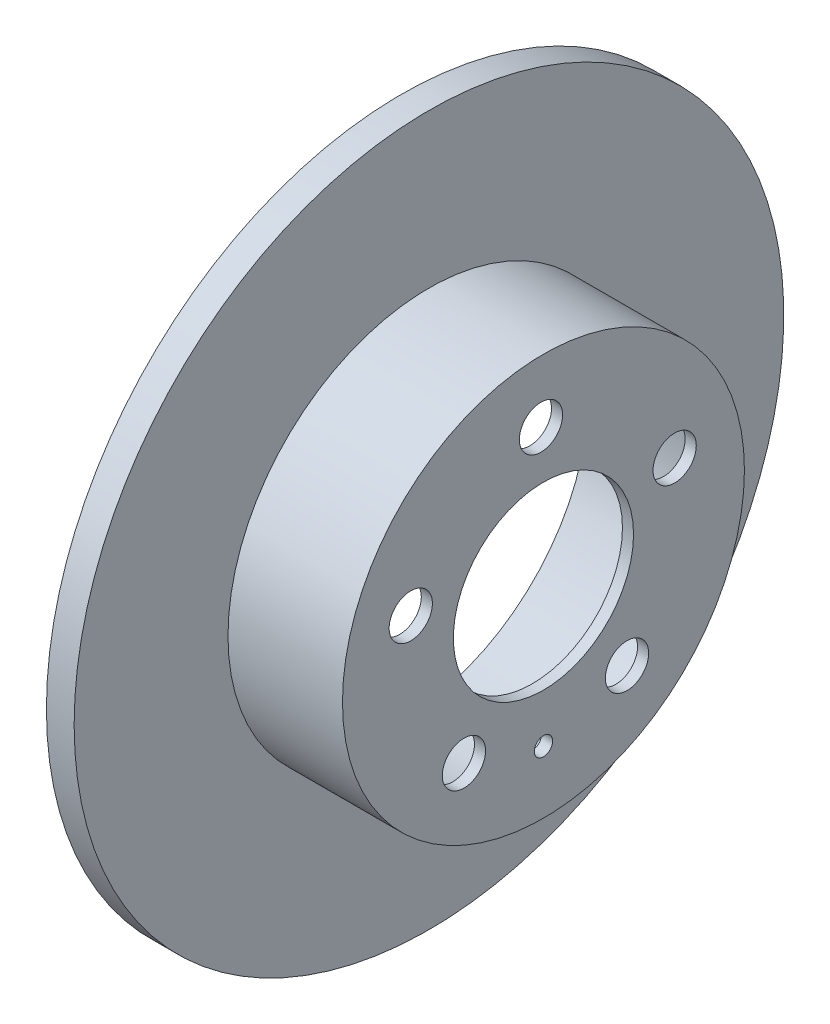
SolidWorks part; units mm, degrees
ref_plane "Płaszczyzna przednia" through (0, 0, 0) normal (0, 0, 1) x (1, 0, 0)
ref_plane "Płaszczyzna górna" through (0, 0, 0) normal (0, 1, 0) x (1, 0, 0)
ref_plane "Płaszczyzna prawa" through (0, 0, 0) normal (1, 0, 0) x (0, 0, -1)
sketch "Szkic1" plane through (0, 0, 0) normal (0, 1, 0) x (1, 0, 0)
  line L1 (0, 0) -> (10, 0)
  line L2 (0, 0) -> (0, 128)
  line L3 (0, 128) -> (10, 128)
  line L4 (10, 0) -> (10, 128)
  dimension "D1" = 10
  dimension "D2" = 128
revolve "Obrót1" add sketch "Szkic1" angle 360 about L1
sketch "Szkic7" plane through (10, 0, 0) normal (1, 0, 0) x (0, 0, -1)
  circle A0 centre (0, 0) radius 72.5
  dimension "D1" = 145
extrude "Dodanie-wyciągnięcie1" add sketch "Szkic7" along normal blind 41.3
sketch "Szkic8" plane through (0, 0, 0) normal (-1, 0, 0) x (0, 0, 1)
  circle A0 centre (0, 0) radius 67.5
  dimension "D1" = 135
sketch "Szkic9" plane through (51.3, 0, 0) normal (1, 0, 0) x (0, 0, -1)
  circle A0 centre (0, 0) radius 32.5
  dimension "D1" = 65
sketch "Szkic10" plane through (51.3, 0, 0) normal (1, 0, 0) x (0, 0, -1)
  line L0 (0, 5.5) -> (0, -5.5) construction
  circle A0 centre (0, 0) radius 50
  circle A1 centre (0, -50) radius 3.3
  circle A2 centre (-28.6826, -40.9549) radius 7.8
  circle A3 centre (-47.8655, 14.6722) radius 7.8
  circle A4 centre (-0.8888, 50.106) radius 7.8
  circle A5 centre (47.3273, 16.3781) radius 7.8
  circle A6 centre (30.1498, -39.9006) radius 7.8
  point P18 (0.008, 0.0602)
  dimension "D1" = 100
  dimension "D2" = 6.6
  dimension "D3" = 15.6
  dimension "D5" = 30.075
  dimension "D6" = 30.1498
  dimension "D4" = 5
extrude "Wytnij-wyciągnięcie7" cut sketch "Szkic8" against normal offset from surface (47.3 mm away) 4 up to face at (51.3, 0, -72.5)
extrude "Wytnij-wyciągnięcie8" cut sketch "Szkic9" against normal up to next
extrude "Wytnij-wyciągnięcie9" cut sketch "Szkic10" against normal up to next contours A0 A5 | A0 A5 | A0 A6 | A0 A6 | A0 A1 | A0 A1 | A0 A2 | A0 A2 | A0 A3 | A0 A3 | A0 A4 | A0 A4
